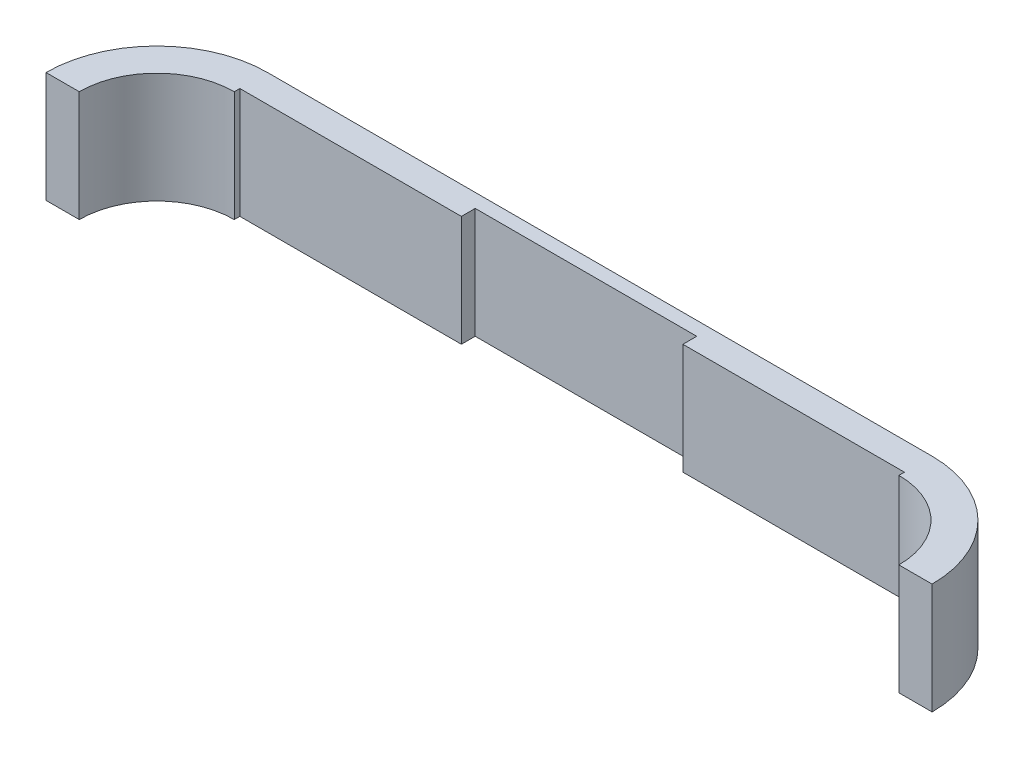
SolidWorks part; units mm, degrees
ref_plane "Front Plane" through (0, 0, 0) normal (0, 0, 1) x (1, 0, 0)
ref_plane "Top Plane" through (0, 0, 0) normal (0, 1, 0) x (1, 0, 0)
ref_plane "Right Plane" through (0, 0, 0) normal (1, 0, 0) x (0, 0, -1)
sketch "Sketch1" plane through (0, 0, 0) normal (0, 1, 0) x (1, 0, 0)
  line L0 (2935.1525, -7133.8462) -> (3035.1525, -7133.8462)
  line L1 (4435.1525, -5733.8462) -> (4435.1525, -5633.8462)
  line L3 (16435.1525, -5733.8462) -> (16435.1525, -5633.8462)
  line L7 (17835.1525, -7133.8462) -> (17935.1525, -7133.8462)
  line L8 (4435.1525, -5633.8462) -> (8435.1525, -5633.8462)
  line L9 (10435.1525, -5383.8462) -> (12435.1525, -5383.8462)
  line L10 (12435.1525, -5383.8462) -> (12435.1525, -5633.8462)
  line L11 (10435.1525, -5383.8462) -> (8435.1525, -5383.8462)
  line L12 (8435.1525, -5383.8462) -> (8435.1525, -5633.8462)
  line L16 (4435.1525, -5133.8462) -> (16435.1525, -5133.8462)
  line L17 (2435.1525, -7133.8462) -> (2935.1525, -7133.8462)
  line L18 (17935.1525, -7133.8462) -> (18435.1525, -7133.8462)
  line L19 (12435.1525, -5633.8462) -> (16435.1525, -5633.8462)
  line L21 (4435.1525, -5633.8462) -> (16435.1525, -5633.8462) construction
  arc A2 (4435.1525, -5733.8462) -> (3035.1525, -7133.8462) centre (4435.1525, -7133.8462) ccw
  arc A3 (16435.1525, -5733.8462) -> (17835.1525, -7133.8462) centre (16435.1525, -7133.8462) cw
  arc A6 (16435.1525, -5633.8462) -> (17935.1525, -7133.8462) centre (16435.1525, -7133.8462) cw
  arc A7 (4435.1525, -5633.8462) -> (2935.1525, -7133.8462) centre (4435.1525, -7133.8462) ccw
  arc A8 (16435.1525, -5133.8462) -> (18435.1525, -7133.8462) centre (16435.1525, -7133.8462) cw
  arc A9 (4435.1525, -5133.8462) -> (2435.1525, -7133.8462) centre (4435.1525, -7133.8462) ccw
  dimension "D1" = 100
  dimension "D4" = 1500
  dimension "D2" = 100
  dimension "D5" = 500
extrude "Boss-Extrude3" add sketch "Sketch1" along normal blind 2000 contours L16 A9 L17 A7 L8 L12 L11 L9 L10 L19 A6 L18 A8 | L1 A7 L0 A2 | A6 L3 A3 L7
